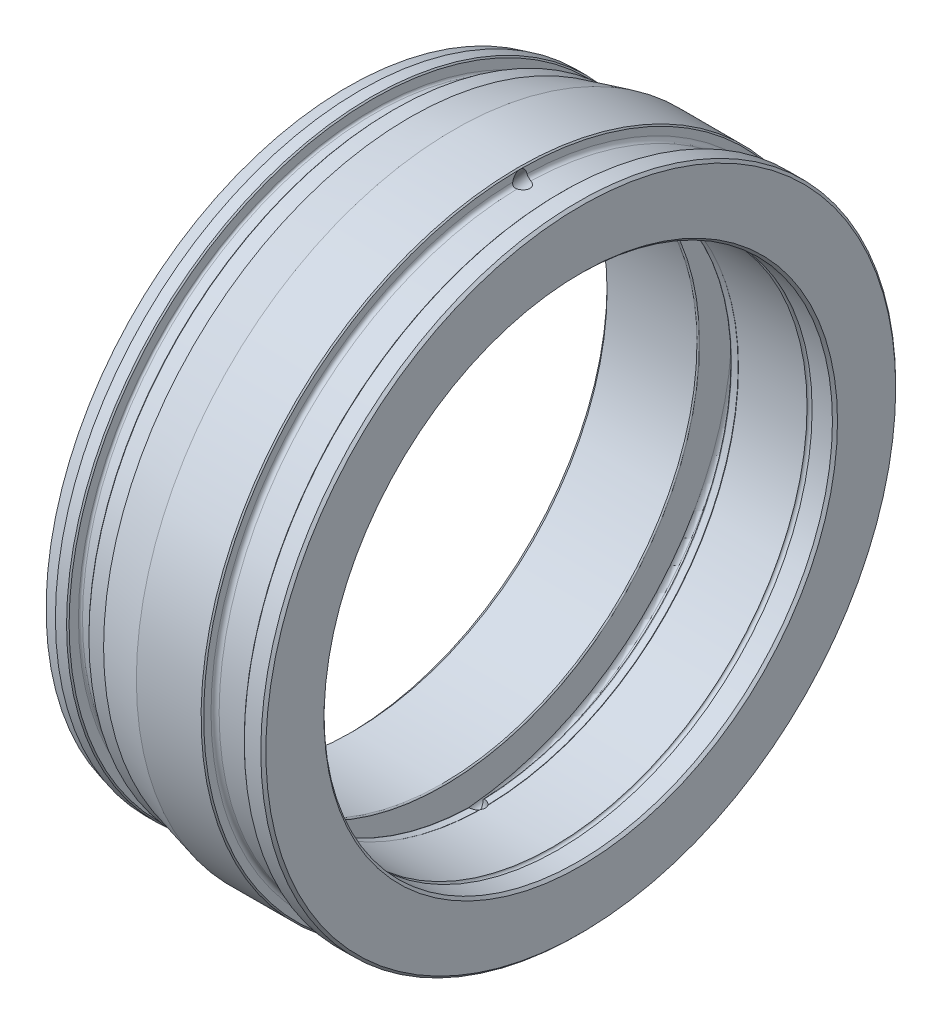
SolidWorks part; units mm, degrees
material "AB01 (C95210) Bronze"
ref_plane "Front Plane" through (0, 0, 0) normal (0, 0, 1) x (1, 0, 0)
ref_plane "Top Plane" through (0, 0, 0) normal (0, 1, 0) x (1, 0, 0)
ref_plane "Right Plane" through (0, 0, 0) normal (1, 0, 0) x (0, 0, -1)
sketch "Sketch1" plane through (0, 0, 0) normal (0, 0, 1) x (1, 0, 0)
  line L0 (0, 50.545) -> (0, 62.0025)
  line L1 (-0.5, 62.5025) -> (-3.75, 62.5025)
  line L2 (-4, 62.2525) -> (-4, 60.8)
  line L3 (-4.8, 60) -> (-11.2, 60)
  line L4 (-12, 60.8) -> (-12, 62.2525)
  line L5 (-12.25, 62.5025) -> (-25, 62.5025)
  line L6 (-43.45, 59.99) -> (-45.95, 59.3201)
  line L7 (-33.7, 59.99) -> (-36.85, 59.99)
  line L8 (-37.1, 59.74) -> (-37.1, 57.9)
  line L9 (-37.5, 57.5) -> (-40.6, 57.5)
  line L10 (-41, 57.9) -> (-41, 59.74)
  line L11 (-41.25, 59.99) -> (-43.45, 59.99)
  line L12 (-45.95, 59.3201) -> (-45.95, 51.125)
  line L13 (-44.95, 50.125) -> (-27, 50.125)
  line L14 (-27, 50.125) -> (-27, 56.75)
  line L15 (-26.2, 57.55) -> (-21.5, 57.55)
  line L16 (-20.7, 56.75) -> (-20.7, 50.125)
  line L17 (-20.7, 50.125) -> (-19.1386, 50.125)
  line L18 (-19.1386, 50.125) -> (-19, 50.045)
  line L19 (-19, 50.045) -> (-5.5, 50.045)
  line L20 (0, 0) -> (-45.7, 0) construction
  line L21 (-4.5, 50.045) -> (-0.5, 50.045)
  line L22 (-12, 60) -> (-20.7, 50.125) construction
  line L23 (-33.7, 59.99) -> (-33.7, 60.25)
  line L24 (-33.7, 60.25) -> (-25, 62.5025)
  line L25 (-41, 59.74) -> (-41.25, 59.99)
  line L26 (-36.85, 59.99) -> (-37.1, 59.74)
  line L27 (-45.95, 51.125) -> (-44.95, 50.125)
  line L28 (0, 62.0025) -> (-0.5, 62.5025)
  line L29 (-0.5, 50.045) -> (0, 50.545)
  line L30 (-3.75, 62.5025) -> (-4, 62.2525)
  line L31 (-12, 62.2525) -> (-12.25, 62.5025)
  arc A0 (-4.5, 50.045) -> (-5.5, 50.045) centre (-5, 49.9325) ccw
  arc A1 (-37.1, 57.9) -> (-37.5, 57.5) centre (-37.5, 57.9) cw
  arc A2 (-40.6, 57.5) -> (-41, 57.9) centre (-40.6, 57.9) cw
  arc A3 (-4, 60.8) -> (-4.8, 60) centre (-4.8, 60.8) cw
  arc A4 (-11.2, 60) -> (-12, 60.8) centre (-11.2, 60.8) cw
  arc A5 (-21.5, 57.55) -> (-20.7, 56.75) centre (-21.5, 56.75) cw
  arc A6 (-27, 56.75) -> (-26.2, 57.55) centre (-26.2, 56.75) cw
  point P1 (0, 62.5025)
  point P3 (-4, 62.5025)
  point P6 (-12, 62.5025)
  point P9 (-37.1, 59.99)
  point P12 (-41, 59.99)
  point P14 (-45.95, 50.125)
  point P21 (0, 50.045)
  dimension "D20" = 0.4
  dimension "D25" = 0.4
  dimension "D27" = 0.8
  dimension "D30" = 0.8
  dimension "D1" = 45.95
  dimension "D2" = 125.005
  dimension "D3" = 119.98
  dimension "D4" = 100.25
  dimension "D5" = 27
  dimension "D6" = 6.3
  dimension "D7" = 19
  dimension "D8" = 100.09
  dimension "D9" = 12
  dimension "D10" = 8
  dimension "D11" = 41
  dimension "D12" = 33.7
  dimension "D13" = 25
  dimension "D14" = 3.9
  dimension "D15" = 115
  dimension "D16" = 120
  dimension "D17" = 115.1
  dimension "D18" = 30
  dimension "D19" = 1
  dimension "D21" = 5
  dimension "D22" = 48.62
  dimension "D23" = 15
  dimension "D24" = 2.5
  dimension "D26" = 120.5
revolve "Revolve1" add sketch "Sketch1" angle 360 about L20
ref_plane "Plane1" through (-12, 60, 0) normal (-0.6611, -0.7503, 0) x (0.7503, -0.6611, 0)
sketch "Sketch2" plane through (-12, 60, 0) normal (-0.6611, -0.7503, 0) x (0.7503, -0.6611, 0)
  circle A0 centre (0, 0) radius 1.5
  dimension "D1" = 3
extrude "Cut-Extrude1" cut sketch "Sketch2" along normal through all and the other way through all
ref_axis "Axis1" through (-44.95, 0, 0) along (1, 0, 0)
pattern_circular "CirPattern1" count 2 over 360 about axis through (-44.95, 0, 0) along (1, 0, 0) of "Cut-Extrude1"
fillet "Fillet1" radius 0.25 3 edges at (-27, 0, -50.125) (-20.7, 0, 50.125) (-20.7, 0, -50.125)
sketch "Sketch3" plane through (-45.95, 0, 0) normal (-1, 0, 0) x (0, 0, 1)
  arc A0 (-42.3649, 30.9756) -> (40.9892, 32.7743) centre (0, 0) cw construction
  text T0 "       11111- XX"
extrude "Cut-Extrude2" cut sketch "Sketch3" against normal blind 0.01
